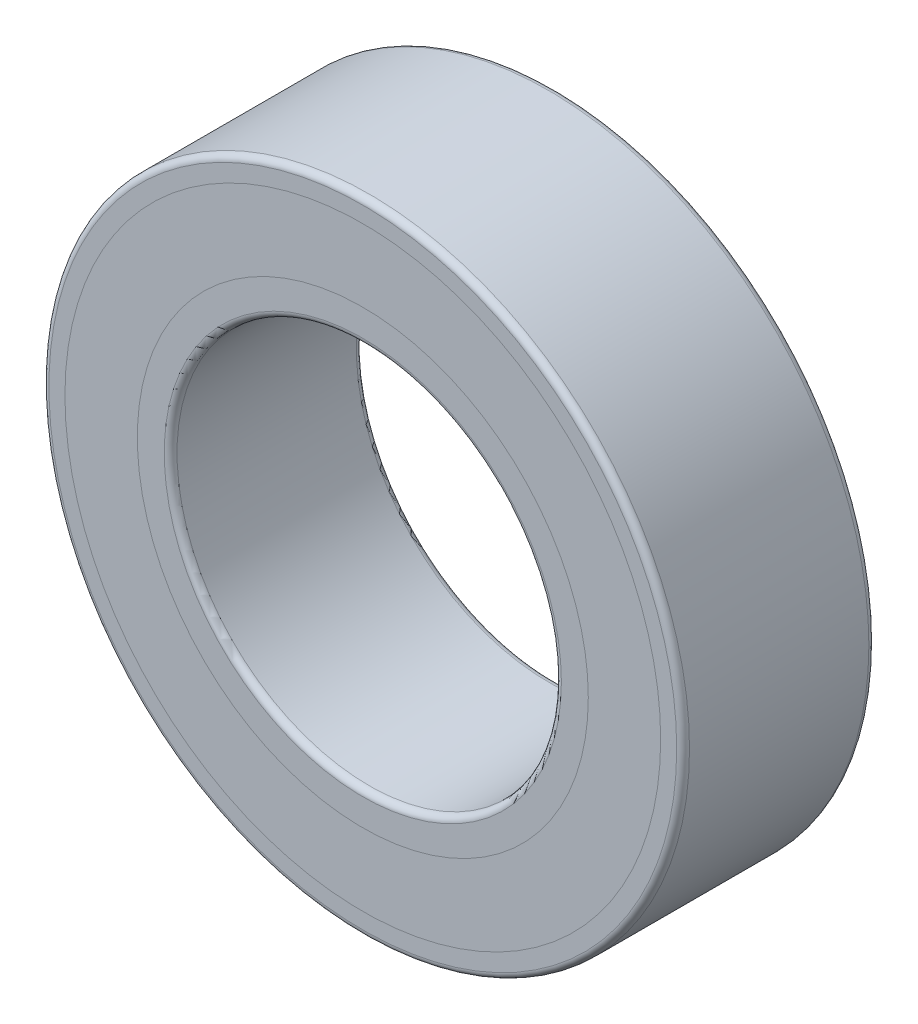
SolidWorks part; units mm, degrees
ref_plane "正面" through (0, 0, 0) normal (0, 0, 1) x (1, 0, 0)
ref_plane "平面" through (0, 0, 0) normal (0, 1, 0) x (1, 0, 0)
ref_plane "右側面" through (0, 0, 0) normal (1, 0, 0) x (0, 0, -1)
sketch "ｽｹｯﾁ1" plane through (0, 0, 0) normal (0, 0, 1) x (1, 0, 0)
  circle A0 centre (0, 0) radius 3
  circle A1 centre (0, 0) radius 5
  dimension "D1" = 10
  dimension "D2" = 6
extrude "ﾎﾞｽ - 押し出し1" add sketch "ｽｹｯﾁ1" along normal blind 3
sketch "ｽｹｯﾁ2" plane through (0, 0, 3) normal (0, 0, 1) x (1, 0, 0)
  circle A0 centre (0, 0) radius 4.65
  circle A1 centre (0, 0) radius 3.52
  dimension "D1" = 7.04
  dimension "D2" = 9.3
split line "分割ﾗｲﾝ1"
fillet "ﾌｨﾚｯﾄ1" radius 0.1 4 edges at (3, 0, 0) (3, 0, 3) (5, 0, 0) (5, 0, 3)
